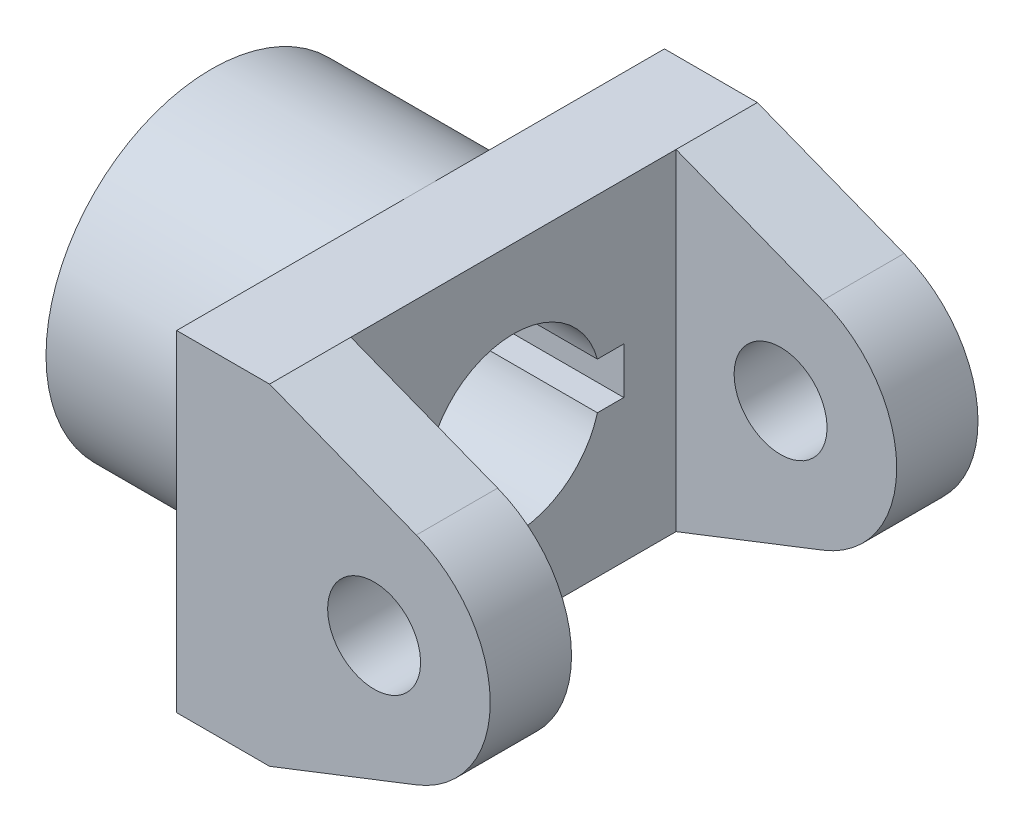
SolidWorks part; units mm, degrees
ref_plane "Front Plane" through (0, 0, 0) normal (0, 0, 1) x (1, 0, 0)
ref_plane "Top Plane" through (0, 0, 0) normal (0, 1, 0) x (1, 0, 0)
ref_plane "Right Plane" through (0, 0, 0) normal (1, 0, 0) x (0, 0, -1)
sketch "Sketch1" plane through (0, 0, 0) normal (0, 0, 1) x (1, 0, 0)
  line L1 (-8, 28.5) -> (8, 28.5)
  line L2 (-8, 28.5) -> (-8, -28.5)
  line L3 (-8, -28.5) -> (8, -28.5)
  line L4 (8, 28.5) -> (8, -28.5)
  line L5 (-8, 28.5) -> (8, -28.5) construction
  line L6 (-8, -28.5) -> (8, 28.5) construction
  point P0 (0, 0)
  dimension "D1" = 16
  dimension "D2" = 57
extrude "Boss-Extrude1" add sketch "Sketch1" along normal mid plane 84
sketch "Sketch3" plane through (0, 0, -42) normal (0, 0, -1) x (-1, 0, 0)
  line L3 (-33.2751, 18.6299) -> (-8, 28.5)
  line L4 (-33.2751, -18.6299) -> (-8, -28.5)
  circle A0 centre (-26, 0) radius 8
  arc A1 (-33.2751, 18.6299) -> (-33.2751, -18.6299) centre (-26, 0) ccw
  line M4 (-8, 28.5) -> (-8, -28.5)
extrude "Boss-Extrude4" add sketch "Sketch3" against normal blind 14 contours L3 A1 L4 A0 M4
mirror "Mirror6" about plane through (0, 0, 0) normal (0, 0, 1) of "Boss-Extrude4"
sketch "Sketch6" plane through (-8, 0, 0) normal (-1, 0, 0) x (0, 0, 1)
  circle A0 centre (0, 0) radius 28.5
  circle A1 centre (0, 0) radius 15
  dimension "D1" = 57
  dimension "D2" = 30
extrude "Boss-Extrude5" add sketch "Sketch6" along normal blind 36 contours A0 | A1
sketch "Sketch8" plane through (-8, 0, 0) normal (-1, 0, 0) x (0, 0, 1)
  circle A0 centre (0, 0) radius 15
extrude "Cut-Extrude1" cut sketch "Sketch8" against normal blind 36
sketch "Sketch9" plane through (-44, 0, 0) normal (-1, 0, 0) x (0, 0, 1)
  line L0 (-15, 0) -> (-19, 0)
  line L1 (-19, 4) -> (-19, -4)
  line L2 (-19, -4) -> (-12.2465, -4)
  line L3 (-12.2465, -4) -> (-12.2465, 4)
  line L4 (-12.2465, 4) -> (-19, 4)
  circle A0 centre (0, 0) radius 15 construction
  point P9 (-19, 0)
  circle M2 centre (0, 0) radius 15
  dimension "D1" = 8
  dimension "D2" = 4
  dimension "D3" = 8
extrude "Cut-Extrude3" cut sketch "Sketch9" against normal through all both and the other way through all contours L1 L2 L0 M2 | L4 L1 L0 M2 | L3 L4 L2 M2
